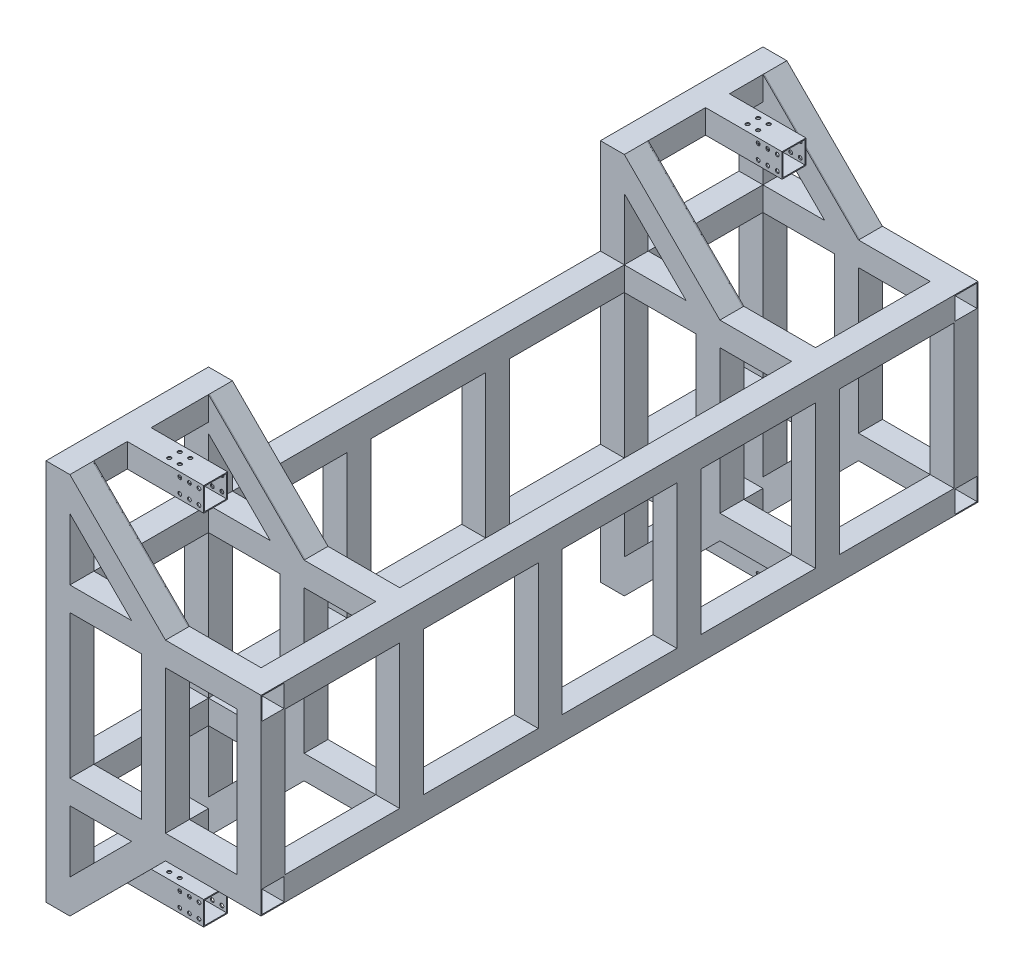
SolidWorks part; units mm, degrees
material "1060 Alloy"
ref_plane "Front Plane" through (0, 0, 0) normal (0, 0, 1) x (1, 0, 0)
ref_plane "Top Plane" through (0, 0, 0) normal (0, 1, 0) x (1, 0, 0)
ref_plane "Right Plane" through (0, 0, 0) normal (1, 0, 0) x (0, 0, -1)
sketch "Sketch1" plane through (0, 0, 0) normal (1, 0, 0) x (0, 0, -1)
  line L0 (-374, 99) -> (-374, 76)
  line L1 (-375, 100) -> (-350, 100)
  line L2 (-375, 100) -> (-375, 75)
  line L3 (-375, 75) -> (-350, 75)
  line L4 (-350, 100) -> (-350, 75)
  line L5 (-374, 76) -> (-351, 76)
  line L6 (-351, 99) -> (-351, 76)
  line L7 (-374, 99) -> (-351, 99)
  line L8 (0, 158.3193) -> (0, -184.8086) construction
  line L9 (-227.5776, 0) -> (199.0756, 0) construction
  line L10 (351, 99) -> (351, 76)
  line L11 (350, 100) -> (375, 100)
  line L12 (350, 100) -> (350, 75)
  line L13 (350, 75) -> (375, 75)
  line L14 (375, 100) -> (375, 75)
  line L15 (351, 76) -> (374, 76)
  line L16 (374, 99) -> (374, 76)
  line L17 (351, 99) -> (374, 99)
  line L18 (351, -76) -> (351, -99)
  line L19 (350, -75) -> (375, -75)
  line L20 (350, -75) -> (350, -100)
  line L21 (350, -100) -> (375, -100)
  line L22 (375, -75) -> (375, -100)
  line L23 (351, -99) -> (374, -99)
  line L24 (374, -76) -> (374, -99)
  line L25 (351, -76) -> (374, -76)
  line L26 (-374, -76) -> (-374, -99)
  line L27 (-375, -75) -> (-350, -75)
  line L28 (-375, -75) -> (-375, -100)
  line L29 (-375, -100) -> (-350, -100)
  line L30 (-350, -75) -> (-350, -100)
  line L31 (-374, -99) -> (-351, -99)
  line L32 (-351, -76) -> (-351, -99)
  line L33 (-374, -76) -> (-351, -76)
  point P37 (-350, 87.5)
  dimension "D1" = 25
  dimension "D2" = 25
  dimension "D4" = 25
  dimension "D5" = 25
  dimension "D7" = 25
  dimension "D8" = 25
  dimension "D10" = 25
  dimension "D11" = 1
  dimension "D12" = 350
  dimension "D13" = 350
  dimension "D14" = 350
  dimension "D15" = 350
  dimension "D16" = 75
  dimension "D17" = 75
  dimension "D18" = 75
  dimension "D19" = 75
  dimension "D3" = 1
  dimension "D6" = 1
  dimension "D9" = 1
extrude "Boss-Extrude1" add sketch "Sketch1" along normal blind 100 and the other way blind 125
sketch "Sketch2" plane through (0, 75, 0) normal (0, -1, 0) x (1, 0, 0)
  line L0 (-125, -375) -> (100, -375) construction
  line L1 (-125, -350) -> (-100, -350)
  line L2 (-125, -350) -> (-125, -375)
  line L3 (-125, -375) -> (-100, -375)
  line L4 (-100, -350) -> (-100, -375)
  line L5 (-125, 350) -> (100, 350) construction
  line L6 (-125, 375) -> (-100, 375)
  line L7 (-125, 375) -> (-125, 350)
  line L8 (-125, 350) -> (-100, 350)
  line L9 (-100, 375) -> (-100, 350)
  line L10 (-125, -350) -> (100, -350) construction
  line L11 (100, -375) -> (75, -375)
  line L12 (100, -375) -> (100, -350)
  line L13 (100, -350) -> (75, -350)
  line L14 (75, -375) -> (75, -350)
  line L15 (-125, 375) -> (100, 375) construction
  line L16 (100, 350) -> (75, 350)
  line L17 (100, 350) -> (100, 375)
  line L18 (100, 375) -> (75, 375)
  line L19 (75, 350) -> (75, 375)
  line L24 (-124, 374) -> (-101, 374)
  line L25 (-101, 374) -> (-101, 351)
  line L26 (-124, 351) -> (-101, 351)
  line L27 (-124, 374) -> (-124, 351)
  line L28 (-124, -351) -> (-101, -351)
  line L29 (-101, -351) -> (-101, -374)
  line L30 (-124, -374) -> (-101, -374)
  line L31 (-124, -351) -> (-124, -374)
  line L32 (99, -374) -> (76, -374)
  line L33 (76, -374) -> (76, -351)
  line L34 (99, -351) -> (76, -351)
  line L35 (99, -374) -> (99, -351)
  line L36 (99, 351) -> (76, 351)
  line L37 (76, 351) -> (76, 374)
  line L38 (99, 374) -> (76, 374)
  line L39 (99, 351) -> (99, 374)
  line L40 (100, 375) -> (100, 350) construction
  line L41 (-125, 375) -> (-125, 350) construction
  dimension "D1" = 25
  dimension "D2" = 25
  dimension "D3" = 25
  dimension "D4" = 25
  dimension "D9" = 0
  dimension "D10" = 25
  dimension "D11" = 25
  dimension "D12" = 0
  dimension "D5" = 1
  dimension "D6" = 1
  dimension "D7" = 1
  dimension "D8" = 1
extrude "Boss-Extrude2" add sketch "Sketch2" along normal blind 150
sketch "Sketch3" plane through (0, 0, -350) normal (0, 0, 1) x (1, 0, 0)
  line L0 (99, 99) -> (76, 99)
  line L1 (-125, 100) -> (-100, 100)
  line L2 (-125, 100) -> (-125, 75)
  line L3 (-125, 75) -> (-100, 75)
  line L4 (-100, 100) -> (-100, 75)
  line L5 (-125, -100) -> (-100, -100)
  line L6 (-125, -100) -> (-125, -75)
  line L7 (-125, -75) -> (-100, -75)
  line L8 (-100, -100) -> (-100, -75)
  line L9 (100, -100) -> (75, -100)
  line L10 (100, -100) -> (100, -75)
  line L11 (100, -75) -> (75, -75)
  line L12 (75, -100) -> (75, -75)
  line L13 (100, 100) -> (75, 100)
  line L14 (100, 100) -> (100, 75)
  line L15 (100, 75) -> (75, 75)
  line L16 (75, 100) -> (75, 75)
  line L17 (76, 99) -> (76, 76)
  line L18 (99, 76) -> (76, 76)
  line L19 (99, 99) -> (99, 76)
  line L20 (-124, 99) -> (-101, 99)
  line L21 (-101, 99) -> (-101, 76)
  line L22 (-124, 76) -> (-101, 76)
  line L23 (-124, 99) -> (-124, 76)
  line L24 (-124, -99) -> (-101, -99)
  line L25 (-101, -99) -> (-101, -76)
  line L26 (-124, -76) -> (-101, -76)
  line L27 (-124, -99) -> (-124, -76)
  line L28 (99, -99) -> (99, -76)
  line L29 (99, -76) -> (76, -76)
  line L30 (76, -99) -> (76, -76)
  line L31 (99, -99) -> (76, -99)
  dimension "D1" = 1
  dimension "D2" = 1
  dimension "D3" = 1
  dimension "D4" = 1
extrude "Boss-Extrude3" add sketch "Sketch3" along normal blind 700
sketch "Sketch4" plane through (75, 0, 0) normal (-1, 0, 0) x (0, 0, 1)
  line L0 (350, -75) -> (-350, -75) construction
  line L1 (-230, -75) -> (-205, -75)
  line L2 (-230, -75) -> (-230, -100)
  line L3 (-230, -100) -> (-205, -100)
  line L4 (-205, -75) -> (-205, -100)
  line L5 (350, -100) -> (-350, -100) construction
  line L6 (-350, -75) -> (-350, -100) construction
  line L28 (-229, -76) -> (-206, -76)
  line L29 (-206, -76) -> (-206, -99)
  line L30 (-229, -99) -> (-206, -99)
  line L31 (-229, -76) -> (-229, -99)
  dimension "D1" = 25
  dimension "D2" = 120
  dimension "D10" = 1
extrude "Boss-Extrude4" add sketch "Sketch4" along normal blind 175
sketch "Sketch5" plane through (0, -100, 0) normal (0, -1, 0) x (1, 0, 0)
  line L0 (-125, 375) -> (-125, -375) construction
  line L35 (-100, -205) -> (-125, -205)
  line L36 (-100, -205) -> (-100, -230)
  line L37 (-100, -230) -> (-125, -230)
  line L38 (-125, -205) -> (-125, -230)
  line L39 (-100, -350) -> (-125, -350)
  line L40 (-100, -350) -> (-100, -375)
  line L41 (-100, -375) -> (-125, -375)
  line L42 (-125, -350) -> (-125, -375)
  line L58 (-101, -206) -> (-101, -229)
  line L59 (-101, -229) -> (-124, -229)
  line L60 (-124, -206) -> (-124, -229)
  line L61 (-101, -206) -> (-124, -206)
  line L62 (-101, -351) -> (-101, -374)
  line L63 (-101, -374) -> (-124, -374)
  line L64 (-124, -351) -> (-124, -374)
  line L65 (-101, -351) -> (-124, -351)
  line L66 (-125, -375) -> (100, -375) construction
  line L67 (-25, -375) -> (0, -375)
  line L68 (-25, -375) -> (-25, -350)
  line L69 (-25, -350) -> (0, -350)
  line L70 (0, -375) -> (0, -350)
  line L71 (-100, -350) -> (75, -350) construction
  line L72 (-100, -230) -> (75, -230) construction
  line L73 (-25, -230) -> (0, -230)
  line L74 (-25, -230) -> (-25, -205)
  line L75 (-25, -205) -> (0, -205)
  line L76 (0, -230) -> (0, -205)
  line L77 (-100, -205) -> (75, -205) construction
  line L90 (-24, -374) -> (-24, -351)
  line L91 (-24, -351) -> (-1, -351)
  line L92 (-1, -374) -> (-1, -351)
  line L93 (-24, -374) -> (-1, -374)
  line L94 (-24, -229) -> (-24, -206)
  line L95 (-24, -206) -> (-1, -206)
  line L96 (-1, -229) -> (-1, -206)
  line L97 (-24, -229) -> (-1, -229)
  line L106 (100, 375) -> (100, -375) construction
  line L108 (-125, -375) -> (100, -375) construction
  dimension "D5" = 25
  dimension "D6" = 25
  dimension "D13" = 100
  dimension "D14" = 100
  dimension "D2" = 0
  dimension "D7" = 1
  dimension "D8" = 1
  dimension "D9" = 1
  dimension "D10" = 1
extrude "Boss-Extrude5" add sketch "Sketch5" along normal blind 100
sketch "Sketch6" plane through (-25, 0, 0) normal (-1, 0, 0) x (0, 0, 1)
  line L0 (-350, -200) -> (-350, -100) construction
  line L1 (-375, -200) -> (-350, -200)
  line L2 (-375, -200) -> (-375, -175)
  line L3 (-375, -175) -> (-350, -175)
  line L4 (-350, -200) -> (-350, -175)
  line L5 (-205, -200) -> (-205, -100) construction
  line L6 (-230, -200) -> (-205, -200)
  line L7 (-230, -200) -> (-230, -175)
  line L8 (-230, -175) -> (-205, -175)
  line L9 (-205, -200) -> (-205, -175)
  line L20 (-374, -199) -> (-374, -176)
  line L21 (-374, -176) -> (-351, -176)
  line L22 (-351, -199) -> (-351, -176)
  line L23 (-374, -199) -> (-351, -199)
  line L24 (-229, -199) -> (-229, -176)
  line L25 (-229, -176) -> (-206, -176)
  line L26 (-206, -199) -> (-206, -176)
  line L27 (-229, -199) -> (-206, -199)
  dimension "D3" = 25
  dimension "D4" = 25
  dimension "D5" = 1
  dimension "D6" = 1
extrude "Boss-Extrude6" add sketch "Sketch6" along normal blind 100
sketch "Sketch7" plane through (0, 0, -350) normal (0, 0, 1) x (1, 0, 0)
  line L1 (-125, -200) -> (-100, -200)
  line L2 (-125, -200) -> (-125, -175)
  line L3 (-125, -175) -> (-100, -175)
  line L4 (-100, -200) -> (-100, -175)
  line L9 (-124, -199) -> (-124, -176)
  line L10 (-124, -176) -> (-101, -176)
  line L11 (-101, -199) -> (-101, -176)
  line L12 (-124, -199) -> (-101, -199)
  dimension "D1" = 1
extrude "Boss-Extrude7" add sketch "Sketch7" along normal blind 120
sketch "Sketch8" plane through (-100, 0, 0) normal (1, 0, 0) x (0, 0, -1)
  line L0 (230, -175) -> (350, -175) construction
  line L1 (290, -175) -> (315, -175)
  line L2 (290, -175) -> (290, -200)
  line L3 (290, -200) -> (315, -200)
  line L4 (315, -175) -> (315, -200)
  line L5 (230, -200) -> (350, -200) construction
  line L6 (230, -200) -> (230, -175) construction
  line L11 (291, -176) -> (291, -199)
  line L12 (291, -199) -> (314, -199)
  line L13 (314, -176) -> (314, -199)
  line L14 (291, -176) -> (314, -176)
  dimension "D1" = 60
  dimension "D3" = 25
  dimension "D2" = 1
extrude "Boss-Extrude8" add sketch "Sketch8" along normal blind 80
sketch "Sketch10" plane through (0, 0, -315) normal (0, 0, -1) x (-1, 0, 0)
  line L0 (20, -175) -> (100, -175) construction
  line L1 (20, -200) -> (100, -200) construction
  line L2 (20, -200) -> (20, -175) construction
  circle A0 centre (25, -180) radius 2
  circle A1 centre (25, -195) radius 2
  circle A2 centre (35, -195) radius 2
  circle A3 centre (35, -180) radius 2
  circle A4 centre (45, -180) radius 2
  circle A5 centre (45, -195) radius 2
  dimension "D1" = 5
  dimension "D2" = 5
  dimension "D3" = 10
  dimension "D4" = 5
  dimension "D5" = 10
  dimension "D6" = 5
  dimension "D7" = 10
  dimension "D8" = 10
  dimension "D9" = 5
  dimension "D10" = 5
  dimension "D11" = 5
  dimension "D12" = 5
extrude "Cut-Extrude1" cut sketch "Sketch10" against normal blind 25
sketch "Sketch20" plane through (0, -200, 0) normal (0, -1, 0) x (1, 0, 0)
  line L2 (-20, -290) -> (-20, -315) construction
  line L4 (-20, -315) -> (-100, -315) construction
  circle A0 centre (-63, -297) radius 2
  circle A1 centre (-63, -308) radius 2
  circle A2 centre (-52, -297) radius 2
  circle A3 centre (-52, -308) radius 2
  point P10 (0, 0)
  dimension "D1" = 7
  dimension "D2" = 11
  dimension "D3" = 7
  dimension "D4" = 11
  dimension "D5" = 43
  dimension "D6" = 43
  dimension "D7" = 32
  dimension "D8" = 32
extrude "Cut-Extrude3" cut sketch "Sketch20" against normal blind 25
sketch "Sketch21" plane through (0, 0, -375) normal (0, 0, -1) x (-1, 0, 0)
  line L0 (125, -200) -> (0, -200) construction
  line L1 (0, -100) -> (100, -100)
  line L2 (0, -100) -> (0, -200)
  line L3 (0, -200) -> (100, -200)
  line L4 (100, -100) -> (100, -200)
  dimension "D1" = 100
extrude "Cut-Extrude5" cut sketch "Sketch21" against normal blind 25
sketch "Sketch18" plane through (0, -75, 0) normal (0, 1, 0) x (1, 0, 0)
  line L0 (-125, -350) -> (-125, 350) construction
  line L1 (-125, -205) -> (-100, -205)
  line L2 (-125, -205) -> (-125, -230)
  line L3 (-125, -230) -> (-100, -230)
  line L4 (-100, -205) -> (-100, -230)
  line L5 (-100, -350) -> (-100, 205) construction
  line L6 (-100, -350) -> (-125, -350) construction
  line L7 (-124, -61) -> (-124, -84)
  line L8 (-125, -60) -> (-100, -60)
  line L9 (-125, -60) -> (-125, -85)
  line L10 (-125, -85) -> (-100, -85)
  line L11 (-100, -60) -> (-100, -85)
  line L12 (-124, -84) -> (-101, -84)
  line L13 (-101, -61) -> (-101, -84)
  line L14 (-124, -61) -> (-101, -61)
  line L15 (-124, -206) -> (-124, -229)
  line L16 (-124, -229) -> (-101, -229)
  line L17 (-101, -206) -> (-101, -229)
  line L18 (-124, -206) -> (-101, -206)
  line L20 (-125, 85) -> (-100, 85)
  line L21 (-125, 85) -> (-125, 60)
  line L22 (-125, 60) -> (-100, 60)
  line L23 (-100, 85) -> (-100, 60)
  line L24 (-125, 230) -> (-100, 230)
  line L25 (-125, 230) -> (-125, 205)
  line L26 (-125, 205) -> (-100, 205)
  line L27 (-100, 230) -> (-100, 205)
  line L29 (-124, 229) -> (-124, 206)
  line L30 (-124, 206) -> (-101, 206)
  line L31 (-101, 229) -> (-101, 206)
  line L32 (-124, 229) -> (-101, 229)
  line L33 (-124, 84) -> (-124, 61)
  line L34 (-124, 61) -> (-101, 61)
  line L35 (-101, 84) -> (-101, 61)
  line L36 (-124, 84) -> (-101, 84)
  line L37 (100, -350) -> (100, 350) construction
  line L38 (100, -230) -> (75, -230)
  line L39 (100, -230) -> (100, -205)
  line L40 (100, -205) -> (75, -205)
  line L41 (75, -230) -> (75, -205)
  line L42 (75, -350) -> (75, 205) construction
  line L43 (100, -350) -> (75, -350) construction
  line L45 (100, -85) -> (75, -85)
  line L46 (100, -85) -> (100, -60)
  line L47 (100, -60) -> (75, -60)
  line L48 (75, -85) -> (75, -60)
  line L49 (100, 60) -> (75, 60)
  line L50 (100, 60) -> (100, 85)
  line L51 (100, 85) -> (75, 85)
  line L52 (75, 60) -> (75, 85)
  line L53 (100, 205) -> (75, 205)
  line L54 (100, 205) -> (100, 230)
  line L55 (100, 230) -> (75, 230)
  line L56 (75, 205) -> (75, 230)
  line L57 (99, -229) -> (99, -206)
  line L58 (99, -206) -> (76, -206)
  line L59 (76, -229) -> (76, -206)
  line L60 (99, -229) -> (76, -229)
  line L61 (99, -84) -> (99, -61)
  line L62 (99, -61) -> (76, -61)
  line L63 (76, -84) -> (76, -61)
  line L64 (99, -84) -> (76, -84)
  line L65 (99, 61) -> (99, 84)
  line L66 (99, 84) -> (76, 84)
  line L67 (76, 61) -> (76, 84)
  line L68 (99, 61) -> (76, 61)
  line L69 (99, 206) -> (99, 229)
  line L70 (99, 229) -> (76, 229)
  line L71 (76, 206) -> (76, 229)
  line L72 (99, 206) -> (76, 206)
  dimension "D1" = 25
  dimension "D2" = 120
  dimension "D3" = 25
  dimension "D4" = 120
  dimension "D5" = 1
  dimension "D7" = 25
  dimension "D8" = 25
  dimension "D9" = 120
  dimension "D10" = 120
  dimension "D11" = 1
  dimension "D13" = 25
  dimension "D14" = 120
  dimension "D15" = 120
  dimension "D16" = 120
  dimension "D17" = 120
  dimension "D18" = 1
  dimension "D6" = 1
  dimension "D12" = 1
  dimension "D19" = 1
  dimension "D20" = 1
  dimension "D21" = 1
extrude "Boss-Extrude21" add sketch "Sketch18" along normal blind 150
ref_plane "Plane1" through (0, 0, -290) normal (0, 0, 1) x (1, 0, 0)
mirror "Mirror1" about plane through (0, 0, -290) normal (0, 0, 1) of "Cut-Extrude5"
mirror "Mirror2" about plane through (0, 0, 0) normal (0, 1, 0) of "Mirror1", "Cut-Extrude5", "Cut-Extrude3", "Cut-Extrude1", "Boss-Extrude8", "Boss-Extrude7", "Boss-Extrude6", "Boss-Extrude5", "Boss-Extrude4", "Boss-Extrude3"
mirror "Mirror3" about plane through (0, 0, 0) normal (0, 0, 1) of "Mirror2", "Boss-Extrude4", "Boss-Extrude5", "Boss-Extrude6", "Boss-Extrude7", "Boss-Extrude8", "Cut-Extrude1", "Cut-Extrude3", "Cut-Extrude5", "Mirror1"
sketch "Sketch19" plane through (0, 75, 0) normal (0, -1, 0) x (1, 0, 0)
  line L0 (-100, -375) -> (75, -375) construction
  line L1 (-25, -375) -> (0, -375)
  line L2 (-25, -375) -> (-25, -350)
  line L3 (-25, -350) -> (0, -350)
  line L4 (0, -375) -> (0, -350)
  line L5 (-100, -350) -> (75, -350) construction
  line L6 (-100, -375) -> (-100, -350) construction
  line L8 (-24, -374) -> (-24, -351)
  line L9 (-24, -351) -> (-1, -351)
  line L10 (-1, -374) -> (-1, -351)
  line L11 (-24, -374) -> (-1, -374)
  line L12 (-100, -205) -> (75, -205) construction
  line L13 (-25, -205) -> (0, -205)
  line L14 (-25, -205) -> (-25, -230)
  line L15 (-25, -230) -> (0, -230)
  line L16 (0, -205) -> (0, -230)
  line L17 (-100, -230) -> (75, -230) construction
  line L18 (-24, -206) -> (-24, -229)
  line L19 (-24, -229) -> (-1, -229)
  line L20 (-1, -206) -> (-1, -229)
  line L21 (-24, -206) -> (-1, -206)
  line L22 (-100, 205) -> (75, 205) construction
  line L23 (-25, 205) -> (0, 205)
  line L24 (-25, 205) -> (-25, 230)
  line L25 (-25, 230) -> (0, 230)
  line L26 (0, 205) -> (0, 230)
  line L27 (-100, 230) -> (75, 230) construction
  line L28 (-100, 350) -> (75, 350) construction
  line L29 (-25, 350) -> (0, 350)
  line L30 (-25, 350) -> (-25, 375)
  line L31 (-25, 375) -> (0, 375)
  line L32 (0, 350) -> (0, 375)
  line L33 (-100, 375) -> (75, 375) construction
  line L34 (75, 205) -> (75, 230) construction
  line L35 (-100, 350) -> (-100, 375) construction
  line L36 (-24, 206) -> (-24, 229)
  line L37 (-24, 229) -> (-1, 229)
  line L38 (-1, 206) -> (-1, 229)
  line L39 (-24, 206) -> (-1, 206)
  line L40 (-24, 351) -> (-24, 374)
  line L41 (-24, 374) -> (-1, 374)
  line L42 (-1, 351) -> (-1, 374)
  line L43 (-24, 351) -> (-1, 351)
  dimension "D1" = 75
  dimension "D2" = 25
  dimension "D3" = 1
  dimension "D5" = 75
  dimension "D6" = 75
  dimension "D4" = 1
  dimension "D7" = 1
  dimension "D8" = 1
extrude "Boss-Extrude22" add sketch "Sketch19" along normal blind 150
sketch "Sketch22" plane through (0, 0, -375) normal (0, 0, -1) x (-1, 0, 0)
  line L0 (0, -75) -> (0, -209.6048) construction
  line L1 (0, -100) -> (100, -200)
  line L2 (100, -100) -> (-100, -100) construction
  line L3 (0, -100) -> (35.3553, -100)
  line L4 (35.3553, -100) -> (100, -164.6447)
  line L5 (100, -200) -> (100, -100) construction
  line L6 (100, -164.6447) -> (100, -200)
  dimension "D1" = 25
extrude "Boss-Extrude23" add sketch "Sketch22" against normal blind 1
sketch "Sketch23" plane through (0, 0, -350) normal (0, 0, 1) x (1, 0, 0)
  line L0 (0, -75) -> (0, -249.5853) construction
  line L1 (-100, -175) -> (-100, -225.0893) construction
  line L2 (-100, -200.0446) -> (0, -100)
  line L3 (-100, -100) -> (75, -100) construction
  line L4 (-100, -164.6814) -> (-35.3475, -100)
  line L5 (-100, -175) -> (-100, -100) construction
  line L6 (-99.1051, -200.9967) -> (-100, -200.0446)
  line L7 (-100, -200.0446) -> (-100, -164.6814)
  line L8 (0, -100) -> (-35.3475, -100)
  line M3 (-100, -100) -> (75, -100)
  dimension "D1" = 25
extrude "Boss-Extrude24" add sketch "Sketch23" against normal blind 1 contours L7 L2 L4 M3
sketch "Sketch26" plane through (0, 0, -351) normal (0, 0, -1) x (-1, 0, 0)
  line L0 (35.3475, -100) -> (100, -164.6814)
  line L1 (100, -164.6814) -> (100, -166.0959)
  line L2 (100, -200) -> (100, -164.6814) construction
  line L3 (100, -166.0959) -> (33.9336, -100)
  line L4 (35.3475, -100) -> (0, -100) construction
  line L5 (33.9336, -100) -> (35.3475, -100)
  line L6 (0, -100) -> (100, -200)
  line L7 (100, -200) -> (100, -198.5858)
  line L8 (100, -198.5858) -> (1.4142, -100)
  line L9 (1.4142, -100) -> (0, -100)
  dimension "D1" = 1
  dimension "D2" = 1
extrude "Boss-Extrude25" add sketch "Sketch26" along normal blind 23
mirror "Mirror4" about plane through (0, 0, -290) normal (0, 0, 1) of "Boss-Extrude25", "Boss-Extrude24", "Boss-Extrude23"
mirror "Mirror5" about plane through (0, 0, 0) normal (0, 1, 0) of "Mirror4", "Boss-Extrude23", "Boss-Extrude24", "Boss-Extrude25"
mirror "Mirror6" about plane through (0, 0, 0) normal (0, 0, 1) of "Mirror5", "Boss-Extrude23", "Boss-Extrude24", "Boss-Extrude25", "Mirror4"
